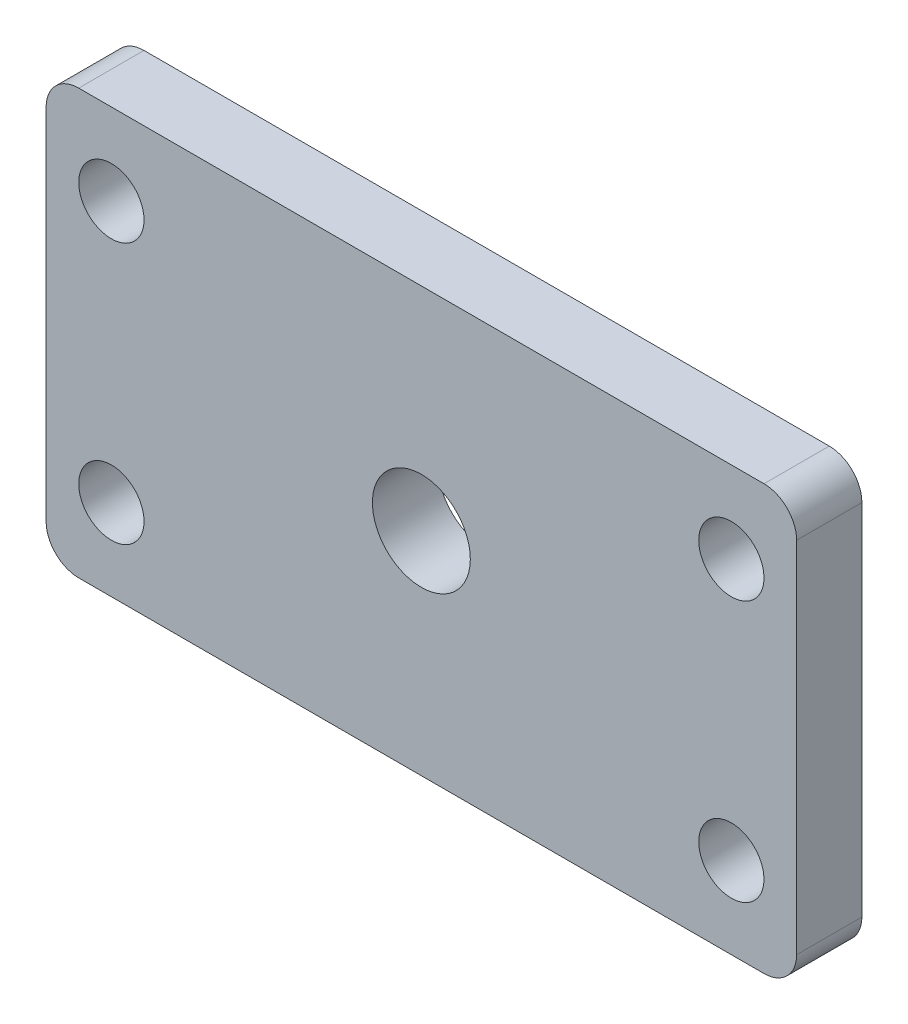
SolidWorks part; units mm, degrees
material "普通碳钢"
ref_plane "前视基准面" through (0, 0, 0) normal (0, 0, 1) x (1, 0, 0)
ref_plane "上视基准面" through (0, 0, 0) normal (0, 1, 0) x (1, 0, 0)
ref_plane "右视基准面" through (0, 0, 0) normal (1, 0, 0) x (0, 0, -1)
sketch "草图1" plane through (0, 0, 0) normal (0, 0, 1) x (1, 0, 0)
  line L0 (0, 6.5) -> (0, -6.5) construction
  line L1 (-11.5, 6.5) -> (11.5, 6.5)
  line L2 (-11.5, 6.5) -> (-11.5, -6.5)
  line L3 (-11.5, -6.5) -> (11.5, -6.5)
  line L4 (11.5, 6.5) -> (11.5, -6.5)
  line L5 (-11.5, 6.5) -> (11.5, -6.5) construction
  line L6 (-11.5, -6.5) -> (11.5, 6.5) construction
  circle A0 centre (-9.5, 4) radius 1
  circle A1 centre (-9.5, -4) radius 1
  circle A2 centre (9.5, -4) radius 1
  circle A3 centre (9.5, 4) radius 1
  circle A4 centre (0, 0) radius 1.5
  point P0 (0, 0)
  dimension "D3" = 2
  dimension "D4" = 2
  dimension "D5" = 8
  dimension "D6" = 2.5
  dimension "D7" = 2.5
  dimension "D8" = 2
  dimension "D9" = 3
  dimension "D1" = 13
  dimension "D2" = 23
extrude "凸台-拉伸1" add sketch "草图1" along normal blind 2
fillet "圆角1" radius 1 4 edges at (11.5, 6.5, 1) (11.5, -6.5, 1) (-11.5, 6.5, 1) (-11.5, -6.5, 1)
